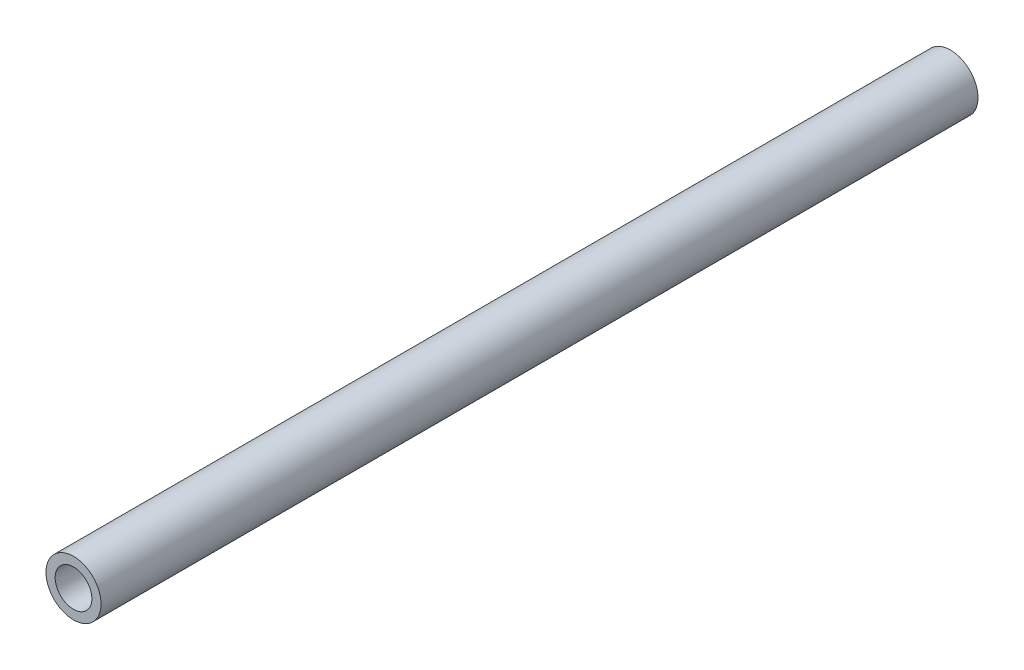
SolidWorks part; units mm, degrees
other "Platform Support Column 1 Left"
ref_plane "Front Plane" through (0, 0, 0) normal (0, 0, 1) x (1, 0, 0)
ref_plane "Top Plane" through (0, 0, 0) normal (0, 1, 0) x (1, 0, 0)
ref_plane "Right Plane" through (0, 0, 0) normal (1, 0, 0) x (0, 0, -1)
sketch3d "Main Profile Sketch datum points"
  point P0 (0, 0, 44.5)
  point P1 (10, 0, 44.5)
  point P2 (0, 10, 44.5)
ref_plane "Main Profile Sketch plane" through (0, 0, 44.5) normal (0, 0, 1) x (1, 0, 0)
sketch "Main Profile Sketch" plane through (0, 0, 44.5) normal (0, 0, 1) x (1, 0, 0)
  circle A0 centre (-255, 51.5) radius 3
  circle A1 centre (-255, 51.5) radius 2
extrude "Main Extrusion" add sketch "Main Profile Sketch" against normal blind 95.5 separate body
